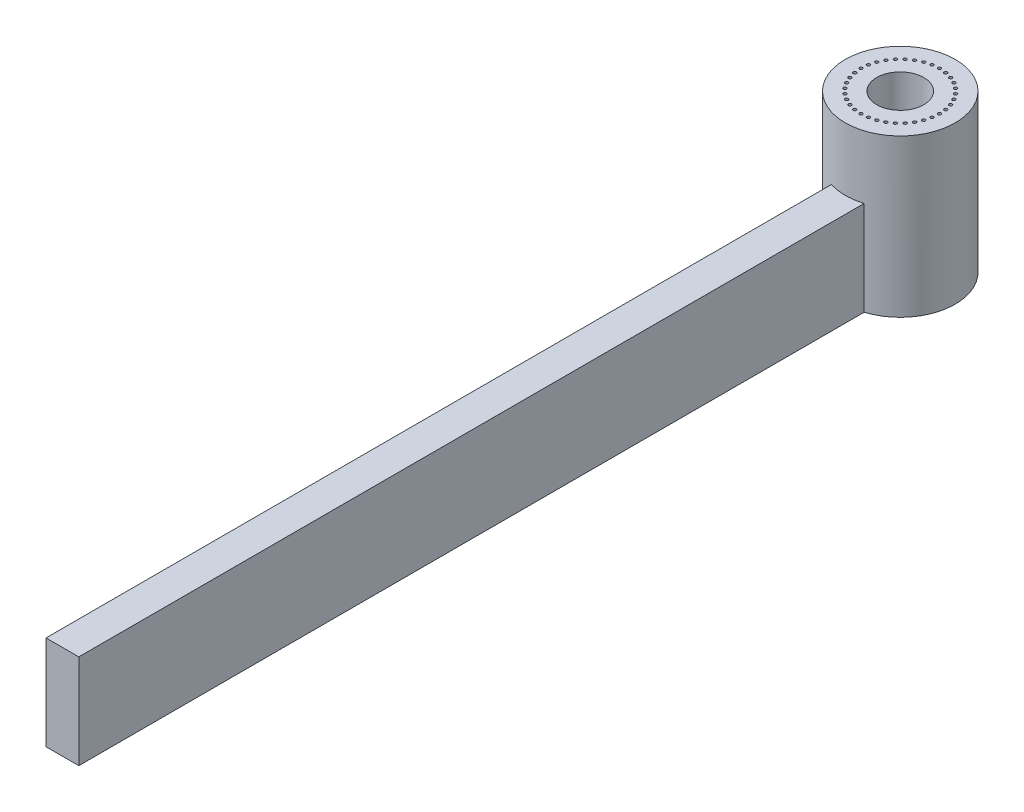
SolidWorks part; units mm, degrees
ref_plane "Front Plane" through (0, 0, 0) normal (0, 0, 1) x (1, 0, 0)
ref_plane "Top Plane" through (0, 0, 0) normal (0, 1, 0) x (1, 0, 0)
ref_plane "Right Plane" through (0, 0, 0) normal (1, 0, 0) x (0, 0, -1)
sketch "Sketch1" plane through (0, 0, 0) normal (0, 1, 0) x (1, 0, 0)
  circle A1 centre (0, 0) radius 3.5
  circle A39 centre (-1.607, 1.9151) radius 0.1
  circle A40 centre (-1.25, 2.1651) radius 0.1
  circle A41 centre (-0.8551, 2.3492) radius 0.1
  circle A42 centre (-0.4341, 2.462) radius 0.1
  circle A43 centre (0, 2.5) radius 0.1
  circle A44 centre (0.4341, 2.462) radius 0.1
  circle A45 centre (0.8551, 2.3492) radius 0.1
  circle A46 centre (1.25, 2.1651) radius 0.1
  circle A47 centre (1.607, 1.9151) radius 0.1
  circle A48 centre (1.9151, 1.607) radius 0.1
  circle A49 centre (2.1651, 1.25) radius 0.1
  circle A50 centre (2.3492, 0.8551) radius 0.1
  circle A51 centre (2.462, 0.4341) radius 0.1
  circle A52 centre (2.3492, -0.8551) radius 0.1
  circle A53 centre (2.462, -0.4341) radius 0.1
  circle A54 centre (1.25, -2.1651) radius 0.1
  circle A55 centre (1.607, -1.9151) radius 0.1
  circle A56 centre (1.9151, -1.607) radius 0.1
  circle A57 centre (2.1651, -1.25) radius 0.1
  circle A58 centre (2.5, 0) radius 0.1
  circle A59 centre (0.4341, -2.462) radius 0.1
  circle A60 centre (0.8551, -2.3492) radius 0.1
  circle A61 centre (-0.4341, -2.462) radius 0.1
  circle A62 centre (-0.8551, -2.3492) radius 0.1
  circle A63 centre (0, -2.5) radius 0.1
  circle A64 centre (-1.25, -2.1651) radius 0.1
  circle A65 centre (-1.9151, -1.607) radius 0.1
  circle A66 centre (-1.607, -1.9151) radius 0.1
  circle A67 centre (-2.462, -0.4341) radius 0.1
  circle A68 centre (-2.3492, -0.8551) radius 0.1
  circle A69 centre (-2.1651, -1.25) radius 0.1
  circle A70 centre (-2.3492, 0.8551) radius 0.1
  circle A71 centre (-2.462, 0.4341) radius 0.1
  circle A72 centre (-2.5, 0) radius 0.1
  circle A73 centre (-1.9151, 1.607) radius 0.1
  circle A74 centre (-2.1651, 1.25) radius 0.1
  circle A76 centre (0, 0) radius 1.5
  dimension "D2" = 7
extrude "Boss-Extrude2" add sketch "Sketch1" along normal blind 10
sketch "Sketch7" plane through (0, 0, 0) normal (0, 1, 0) x (1, 0, 0)
  line L1 (-1.0438, -3.3407) -> (1.0438, -3.3407)
  line L2 (-1.0438, -3.3407) -> (-1.0438, -53.3407)
  line L3 (-1.0438, -53.3407) -> (1.0438, -53.3407)
  line L4 (1.0438, -3.3407) -> (1.0438, -53.3407)
  circle A0 centre (0, 0) radius 3.5 construction
  point P4 (0, 0)
  point P5 (0, 0)
  point P6 (-2.1488, -2.7628)
  point P9 (1.7917, -3.0066)
  point P10 (1.0438, -30.9452)
  dimension "D1" = 50
extrude "Boss-Extrude4" add sketch "Sketch7" along normal blind 6
